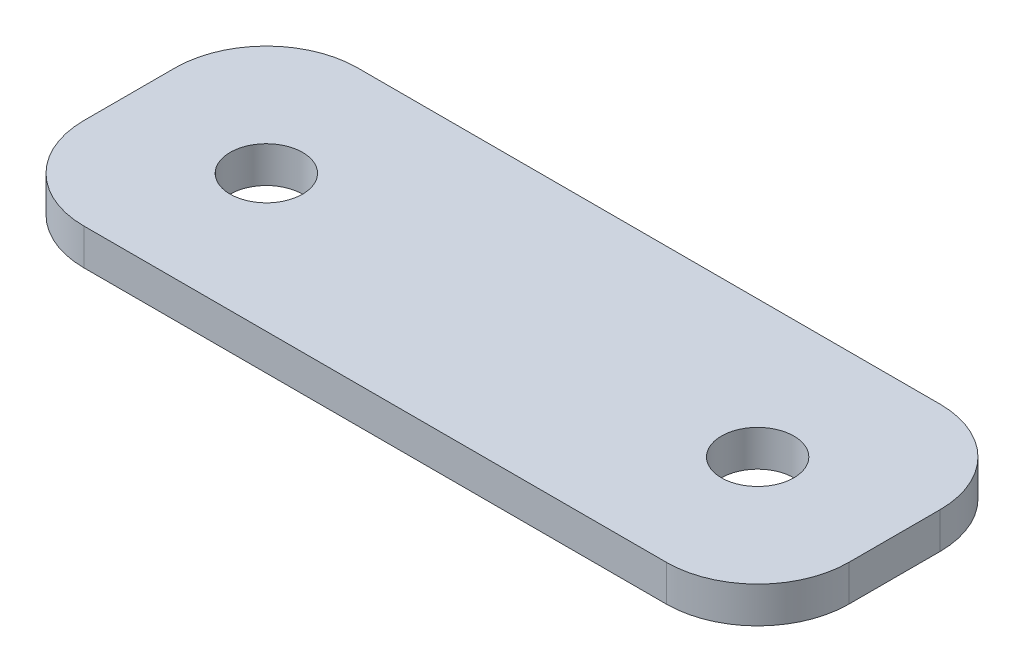
SolidWorks part; units mm, degrees
ref_plane "Front Plane" through (0, 0, 0) normal (0, 0, 1) x (1, 0, 0)
ref_plane "Top Plane" through (0, 0, 0) normal (0, 1, 0) x (1, 0, 0)
ref_plane "Right Plane" through (0, 0, 0) normal (1, 0, 0) x (0, 0, -1)
sketch "Sketch1" plane through (0, 0, 0) normal (0, 1, 0) x (1, 0, 0)
  line L0 (-10.765, 0) -> (10.765, 0) construction
  line L1 (16.765, -6) -> (-16.765, -6)
  line L2 (16.765, -6) -> (16.765, 6)
  line L3 (16.765, 6) -> (-16.765, 6)
  line L4 (-16.765, -6) -> (-16.765, 6)
  line L5 (16.765, -6) -> (-16.765, 6) construction
  line L6 (16.765, 6) -> (-16.765, -6) construction
  circle A0 centre (-10.765, 0) radius 1.5875
  circle A1 centre (10.765, 0) radius 1.5875
  circle A2 centre (-10.765, 0) radius 5 construction
  point P0 (0, 0)
  point P8 (0, 0)
  dimension "D1" = 3.175
  dimension "D4" = 10
  dimension "D2" = 21.53
  dimension "D3" = 12
  dimension "D5" = 6
extrude "Boss-Extrude1" add sketch "Sketch1" along normal mid plane 1.5875
fillet "Fillet1" radius 4 4 edges at (16.765, 0, 6) (16.765, 0, -6) (-16.765, 0, -6) (-16.765, 0, 6)
